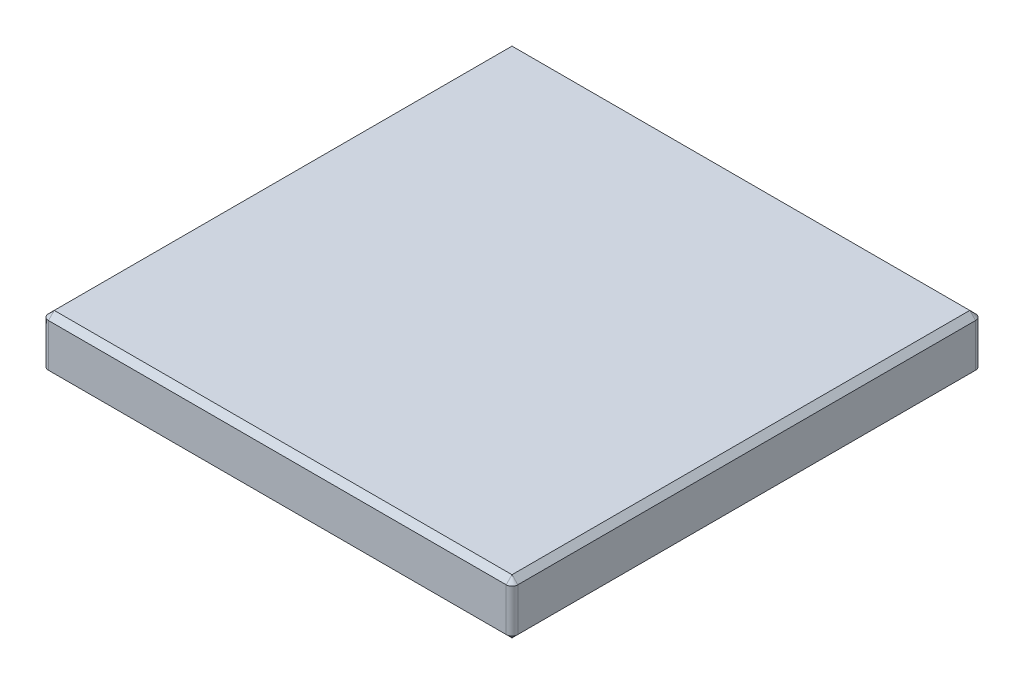
SolidWorks part; units mm, degrees
ref_plane "Front Plane" through (0, 0, 0) normal (0, 0, 1) x (1, 0, 0)
ref_plane "Top Plane" through (0, 0, 0) normal (0, 1, 0) x (1, 0, 0)
ref_plane "Right Plane" through (0, 0, 0) normal (1, 0, 0) x (0, 0, -1)
sketch "Sketch1" plane through (0, 0, 0) normal (0, 1, 0) x (1, 0, 0)
  line L1 (-201.5, -201.5) -> (201.5, -201.5)
  line L2 (-201.5, -201.5) -> (-201.5, 201.5)
  line L3 (-201.5, 201.5) -> (201.5, 201.5)
  line L4 (201.5, -201.5) -> (201.5, 201.5)
  line L5 (-201.5, -201.5) -> (201.5, 201.5) construction
  line L6 (-201.5, 201.5) -> (201.5, -201.5) construction
  point P0 (0, 0)
  dimension "D1" = 403
extrude "Boss-Extrude1" add sketch "Sketch1" along normal blind 47
fillet "Fillet1" radius 5 4 edges at (201.5, 23.5, -201.5) (201.5, 23.5, 201.5) (-201.5, 23.5, -201.5) (-201.5, 23.5, 201.5)
chamfer "Chamfer1" distance 5 angle 45 16 edges at (0, 0, -201.5) (-201.5, 0, 0) (0, 0, 201.5) (201.5, 0, 0) (201.5, 47, 0) (0, 47, -201.5) (-201.5, 47, 0) (0, 47, 201.5) (-200.0355, 0, 200.0355) (-200.0355, 0, -200.0355) (200.0355, 0, 200.0355) (200.0355, 0, -200.0355) (-200.0355, 47, -200.0355) (200.0355, 47, -200.0355) (-200.0355, 47, 200.0355) (200.0355, 47, 200.0355)
sketch "Sketch2" plane through (0, 0, 0) normal (0, 1, 0) x (1, 0, 0)
  circle A0 centre (0, 0) radius 5
  dimension "D1" = 10
